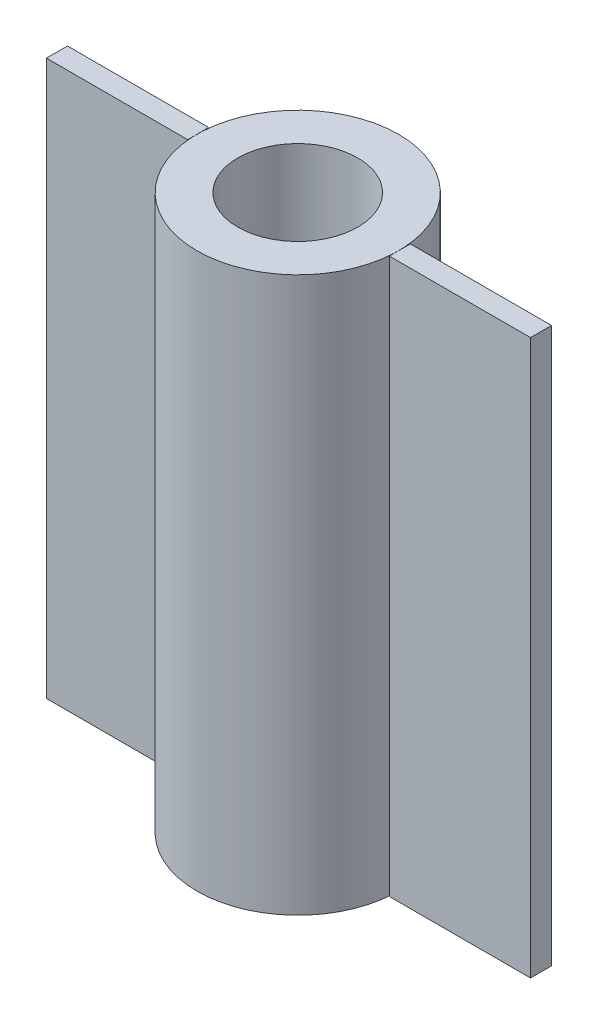
SolidWorks part; units mm, degrees
ref_plane "Front Plane" through (0, 0, 0) normal (0, 0, 1) x (1, 0, 0)
ref_plane "Top Plane" through (0, 0, 0) normal (0, 1, 0) x (1, 0, 0)
ref_plane "Right Plane" through (0, 0, 0) normal (1, 0, 0) x (0, 0, -1)
sketch "Sketch2" plane through (0, 0, 0) normal (0, 1, 0) x (1, 0, 0)
  circle A0 centre (0, 0) radius 12.7
extrude "Boss-Extrude1" add sketch "Sketch2" along normal blind 69.85 contours A0
ref_plane "Plane1" through (0, 69.85, 0) normal (0, 1, 0) x (1, 0, 0)
sketch "Sketch5" plane through (0, 69.85, 0) normal (0, 1, 0) x (1, 0, 0)
  circle A0 centre (0, 0) radius 7.5574
extrude "Cut-Extrude1" cut sketch "Sketch5" against normal blind 60.96 contours A0
ref_plane "Plane2" through (12.7, 0, 0) normal (1, 0, 0) x (0, 0, -1)
sketch "Sketch7" plane through (12.7, 0, 0) normal (1, 0, 0) x (0, 0, -1)
  line L0 (13.97, 69.85) -> (-13.97, 69.85) construction
  line L1 (-1.1651, 69.85) -> (1.4828, 69.85)
  line L2 (-1.1651, 69.85) -> (-1.1651, 0)
  line L3 (-1.1651, 0) -> (1.4828, 0)
  line L4 (1.4828, 69.85) -> (1.4828, 0)
  line L5 (13.97, 0) -> (-13.97, 0) construction
extrude "Boss-Extrude2" add sketch "Sketch7" along normal blind 17.78 separate body contours L4 L3 L2 L1
mirror "Mirror3" about plane through (0, 0, 0) normal (1, 0, 0) of bodies 103
